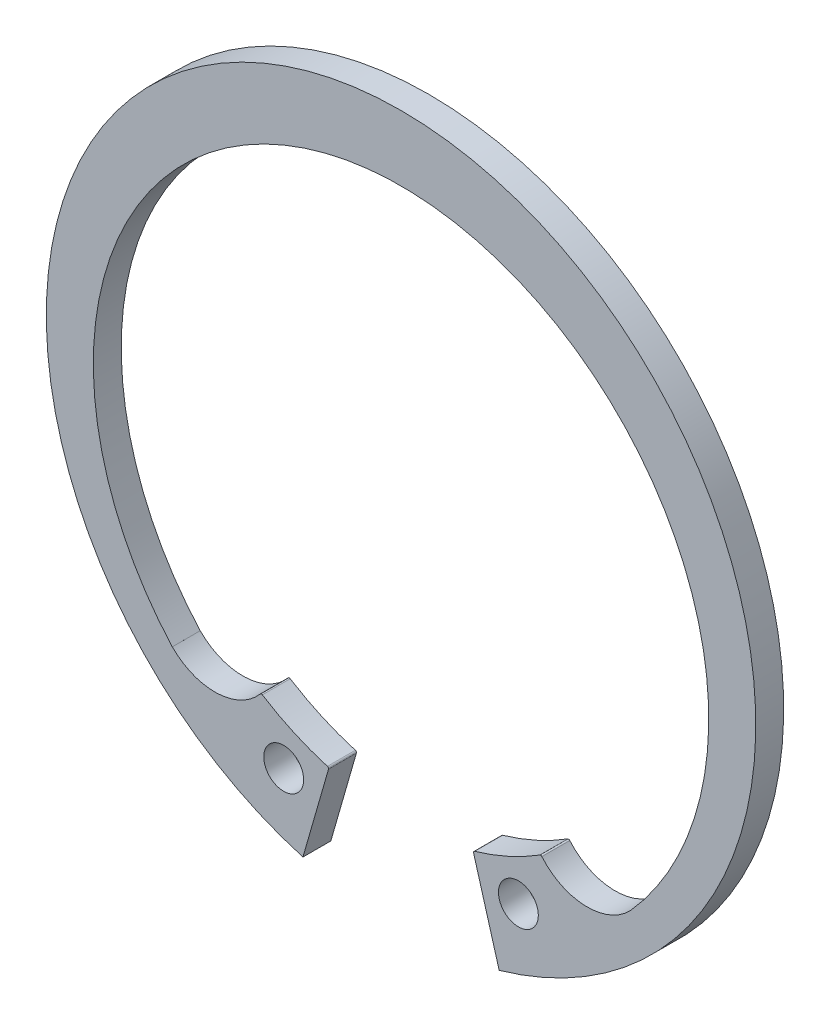
SolidWorks part; units mm, degrees
ref_plane "Plane1" through (0, 0, 0) normal (0, 0, 1) x (1, 0, 0)
ref_plane "Plane2" through (0, 0, 0) normal (0, 1, 0) x (1, 0, 0)
ref_plane "Plane3" through (0, 0, 0) normal (1, 0, 0) x (0, 0, -1)
extrude "Body" add sketch "BodySke" against normal blind 1.75
sketch "BodySke" plane through (0, 0, 0) normal (0, 0, 1) x (1, 0, 0)
  line L0 (-1.5431, 0) -> (1.5431, 0) construction
  line L1 (0, 0) -> (0, 18.15) construction
  line L2 (6.1547, -21.3818) -> (5.1256, -17.8067)
  line L3 (-6.1547, -21.3818) -> (-5.1256, -17.8067)
  line L4 (0, 0) -> (13.5796, -17.6255) construction
  line L5 (0, 0) -> (-13.5796, -17.6255) construction
  line L6 (-7.0141, -15.9623) -> (-7.7057, -18.3648) construction
  line L7 (7.1523, -16.4422) -> (7.5675, -17.8848) construction
  arc A0 (-5.1256, -17.8067) -> (-9.1342, -15.661) centre (-7.3599, -17.1635) ccw
  arc A1 (9.1342, -15.661) -> (5.1256, -17.8067) centre (7.3599, -17.1635) ccw
  arc A2 (12.3284, -16.0015) -> (-12.3284, -16.0015) centre (0, -1.151) ccw construction
  arc A3 (6.1547, -21.3818) -> (-6.1547, -21.3818) centre (0, 0) ccw
  circle A4 centre (7.3599, -17.1635) radius 1.25
  circle A5 centre (-7.3599, -17.1635) radius 1.25
  circle A6 centre (7.3599, -17.1635) radius 2.325 construction
  arc A7 (12.4024, -15.9399) -> (-12.4024, -15.9399) centre (0, -1.151) ccw
  arc A8 (-7.3599, -17.1635) -> (7.3599, -17.1635) centre (0, 0) ccw construction
  arc A9 (-12.4024, -15.9399) -> (-9.1342, -15.661) centre (-10.9084, -14.1584) ccw
  arc A10 (9.1342, -15.661) -> (12.4024, -15.9399) centre (10.9084, -14.1584) ccw
  dimension "GrooveDia" = 44.5
  dimension "TipRad" = 2.325
  dimension "HoleOffsetRad" = 18.675
  dimension "HoleDia" = 2.5
  dimension "FilletRad" = 2.325
  dimension "LargeRad" = 18.15
  dimension "SmallRad" = 20.2
  dimension "SmallAngle" = 75.225
  dimension "GapAngle" = 32.117
sketch "Clipboard" plane through (0, 0, 0) normal (0, 0, 1) x (1, 0, 0)
  line L0 (0, 0) -> (4.1, 0)
  line L1 (0, 0) -> (0, 2.05)
  line L2 (0, 0) -> (0, -5.9)
  circle A0 centre (0, 0) radius 1.25
  circle A1 centre (0, 0) radius 21
  dimension "HoleDia" = 2.5
  dimension "BoreDia" = 42
  dimension "LargeSection" = 4.1
  dimension "SmallSection" = 2.05
  dimension "LugSection" = 5.9
sketch "ModLugSke" plane through (0, 0, 0) normal (0, 0, 1) x (1, 0, 0)
  line L0 (6.1547, -21.3818) -> (4.5503, -15.8078)
  line L1 (-6.1547, -21.3818) -> (-4.5503, -15.8078)
  line L2 (11.6776, -11.4436) -> (15.8915, -15.5731) construction
  line L3 (-11.6776, -11.4436) -> (-15.8915, -15.5731) construction
  line L4 (-6.1547, -21.3818) -> (-5.1256, -17.8067) construction
  line L5 (5.1256, -17.8067) -> (6.1547, -21.3818) construction
  line L6 (0, 0) -> (0, -18.0732) construction
  line L7 (14.3451, -14.0577) -> (15.8915, -15.5731)
  line L8 (-15.8915, -15.5731) -> (-14.3451, -14.0577)
  arc A0 (6.1547, -21.3818) -> (15.8915, -15.5731) centre (0, 0) ccw
  arc A1 (-8.7018, -13.842) -> (-4.6181, -15.6842) centre (0, 0) ccw
  arc A2 (6.1547, -21.3818) -> (-6.1547, -21.3818) centre (0, 0) ccw construction
  arc A3 (9.1342, -15.661) -> (5.1256, -17.8067) centre (7.3599, -17.1635) ccw construction
  arc A4 (-8.7018, -13.842) -> (-8.8313, -13.8619) centre (-8.7551, -13.9266) ccw
  arc A5 (-14.3451, -14.0577) -> (-8.8313, -13.8619) centre (-11.6776, -11.4436) ccw
  arc A6 (12.4024, -15.9399) -> (-12.4024, -15.9399) centre (0, -1.151) ccw construction
  arc A7 (8.8313, -13.8619) -> (14.3451, -14.0577) centre (11.6776, -11.4436) ccw
  arc A8 (4.6181, -15.6842) -> (8.7018, -13.842) centre (0, 0) ccw
  arc A9 (-15.8915, -15.5731) -> (-6.1547, -21.3818) centre (0, 0) ccw
  circle A10 centre (-7.3599, -17.1635) radius 1.25
  circle A11 centre (-7.3599, -17.1635) radius 1.25 construction
  circle A12 centre (7.3599, -17.1635) radius 1.25
  circle A13 centre (7.3599, -17.1635) radius 1.25 construction
  arc A14 (-4.6181, -15.6842) -> (-4.5503, -15.8078) centre (-4.6464, -15.7802) cw
  arc A15 (4.6181, -15.6842) -> (4.5503, -15.8078) centre (4.6464, -15.7802) ccw
  arc A16 (8.7018, -13.842) -> (8.8313, -13.8619) centre (8.7551, -13.9266) cw
  point P43 (4.5227, -15.712)
  dimension "D1" = 0.1
  dimension "LugAng" = 64.312
extrude "ModLug" add sketch "ModLugSke" against normal through all
sketch "UnlSke" [suppressed] plane through (0, 0, 0) normal (0, 0, 1) x (1, 0, 0)
  line L0 (2.1178, -8.3352) -> (3.2259, -12.6966)
  line L1 (-2.1178, -8.3352) -> (-3.2259, -12.6966)
  line L2 (-3.2259, -12.6966) -> (-2.1422, -8.4315) construction
  line L3 (2.1422, -8.4315) -> (3.2259, -12.6966) construction
  arc A0 (2.1178, -8.3352) -> (-2.1178, -8.3352) centre (0, 0) ccw
  arc A1 (3.2259, -12.6966) -> (-3.2259, -12.6966) centre (0, 0) ccw
  arc A2 (3.2259, -12.6966) -> (-3.2259, -12.6966) centre (0, 0) ccw construction
  circle A4 centre (-4.4431, -9.5688) radius 1
  circle A5 centre (4.4431, -9.5688) radius 1
  circle A6 centre (4.4431, -9.5688) radius 1 construction
  circle A7 centre (-4.4431, -9.5688) radius 1 construction
  arc A8 (2.2134, -8.3103) -> (4.9183, -7.0548) centre (0, 0) ccw construction
extrude "Unlug" [suppressed] add sketch "UnlSke" against normal through all
equation "' \"BoreDia@Clipboard\" = 8"
equation "' \"Thickness@Body\" = 0.8"
equation "' \"GrooveDia@BodySke\" = 8.4"
equation "' \"LugSection@Clipboard\" = 2.4"
equation "' \"LargeSection@Clipboard\" = 1.1"
equation "' \"HoleDia@Clipboard\" = 1.0"
equation "' \"BoreDia@Clipboard\" = 25"
equation "' \"Thickness@Body\" = 1.2"
equation "' \"GrooveDia@BodySke\" = 26.2"
equation "' \"LugSection@Clipboard\" = 4.5"
equation "' \"LargeSection@Clipboard\" = 2.7"
equation "' \"HoleDia@Clipboard\" = 2"
equation "\"SmallSection@Clipboard\" = \"LargeSection@Clipboard\" * 0.5"
equation "\"TipRad@BodySke\" = (\"LugSection@Clipboard\" - (\"GrooveDia@BodySke\" / 2  -  \"BoreDia@Clipboard\" / 2 ) ) / 2"
equation "\"HoleOffsetRad@BodySke\" = (\"GrooveDia@BodySke\" / 2) - \"LugSection@Clipboard\"  + \"TipRad@BodySke\""
equation "\"LargeRad@BodySke\" =  \"GrooveDia@BodySke\" / 2 -  \"LargeSection@Clipboard\""
equation "\"SmallRad@BodySke\" =  \"GrooveDia@BodySke\" / 2 -  \"SmallSection@Clipboard\""
equation "\"HoleDia@BodySke\" =  \"HoleDia@Clipboard\""
equation "\"FilletRad@BodySke\" = \"TipRad@BodySke\" * 1.0"
equation "\"GapAngle@BodySke\" = 360 - 0.965 * 360 * ( \"BoreDia@Clipboard\" /  \"GrooveDia@BodySke\")"
equation "\"LugAng@ModLugSke\" = \"GapAngle@BodySke\"  + 2 * 360 * (\"LugSection@Clipboard\" / (\"BoreDia@Clipboard\" * 3.1416))"
